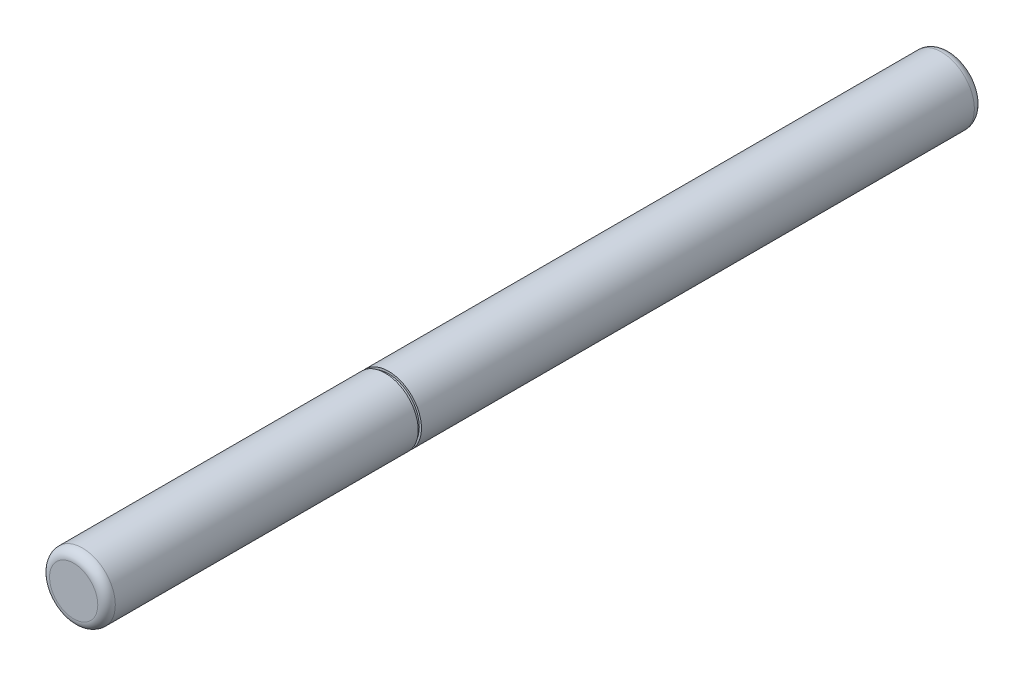
SolidWorks part; units mm, degrees
ref_plane "Front Plane" through (0, 0, 0) normal (0, 0, 1) x (1, 0, 0)
ref_plane "Top Plane" through (0, 0, 0) normal (0, 1, 0) x (1, 0, 0)
ref_plane "Right Plane" through (0, 0, 0) normal (1, 0, 0) x (0, 0, -1)
sketch "Sketch1" plane through (0, 0, 0) normal (0, 0, 1) x (1, 0, 0)
  circle A0 centre (0, 0) radius 1.5
extrude "Boss-Extrude1" add sketch "Sketch1" along normal blind 40
fillet "Fillet1" radius 0.4 2 edges at (1.5, 0, 0) (1.5, 0, 40)
ref_plane "Plane1" through (0, 0, 25.78) normal (0, 0, 1) x (1, 0, 0)
sketch "Sketch2" plane through (0, 0, 25.78) normal (0, 0, 1) x (1, 0, 0)
  circle A0 centre (0, 0) radius 2.9727
  circle A1 centre (0, 0) radius 1.4
extrude "Cut-Extrude1" cut sketch "Sketch2" against normal blind 0.15
